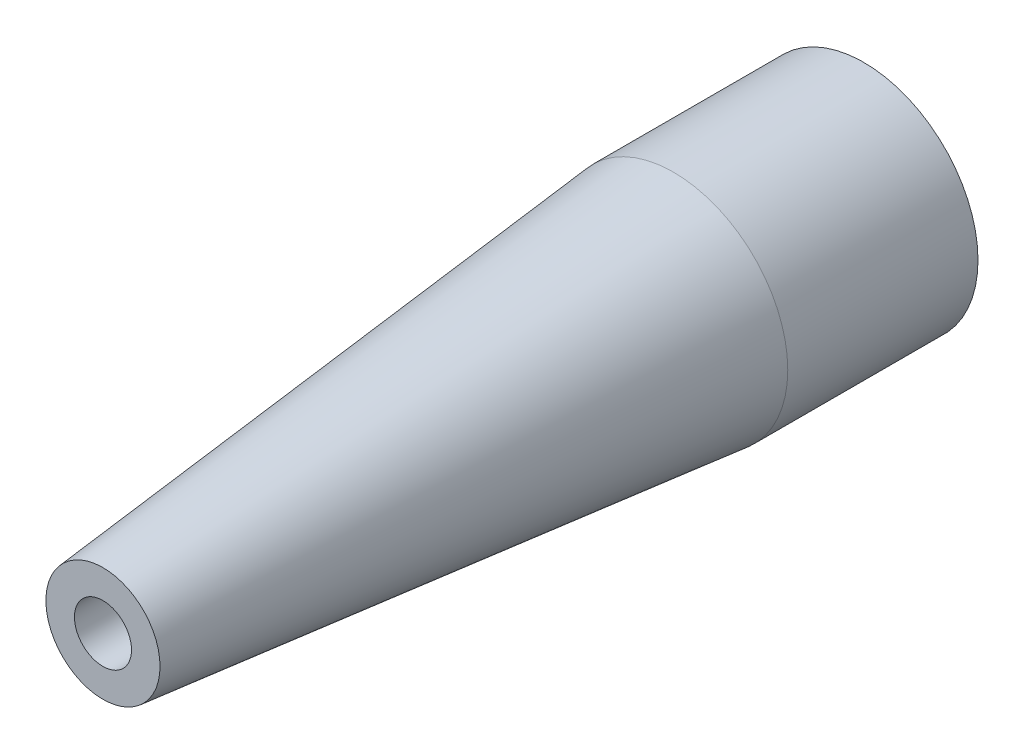
SolidWorks part; units mm, degrees
ref_plane "Plan de face" through (0, 0, 0) normal (0, 0, 1) x (1, 0, 0)
ref_plane "Plan de dessus" through (0, 0, 0) normal (0, 1, 0) x (1, 0, 0)
ref_plane "Plan de droite" through (0, 0, 0) normal (1, 0, 0) x (0, 0, -1)
sketch "Esquisse1" plane through (0, 0, 0) normal (0, 0, 1) x (1, 0, 0)
  circle A0 centre (0, 0) radius 3
  circle A1 centre (0, 0) radius 0.75
  dimension "D1" = 6
  dimension "D2" = 1.5
extrude "Boss.-Extru.1" add sketch "Esquisse1" along normal blind 20
chamfer "Chanfrein1" distance 15 distance2 1.5 1 edges at (3, 0, 20)
